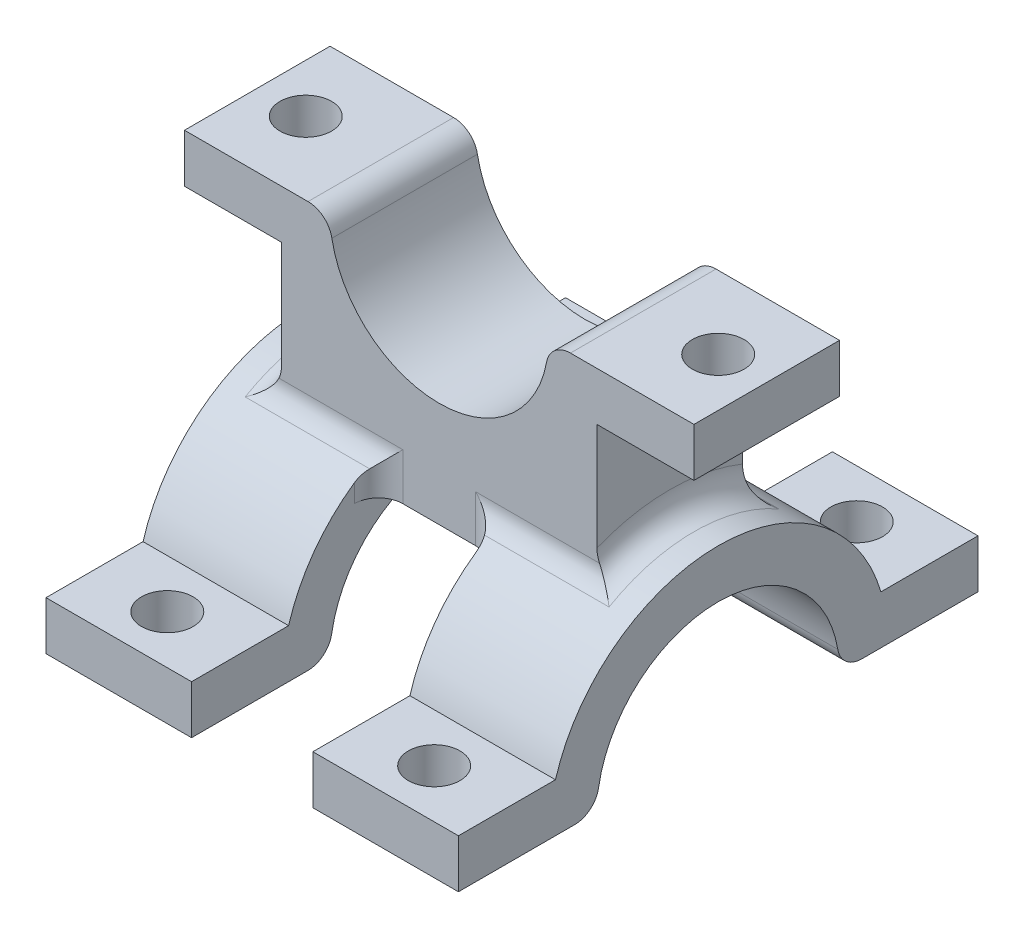
SolidWorks part; units mm, degrees
ref_plane "Front Plane" through (0, 0, 0) normal (0, 0, 1) x (1, 0, 0)
ref_plane "Top Plane" through (0, 0, 0) normal (0, 1, 0) x (1, 0, 0)
ref_plane "Right Plane" through (0, 0, 0) normal (1, 0, 0) x (0, 0, -1)
sketch "Sketch1" plane through (0, 0, 0) normal (0, 0, 1) x (1, 0, 0)
  line L0 (0, 0) -> (0, 50000) construction
  line L1 (-76.4961, 74.3576) -> (-37.8039, 99.7576) construction
  line L5 (-37.8039, 99.7576) -> (-241.0039, 99.7576) construction
  line L6 (-182.9308, 127.7976) -> (-163.8808, 127.7976)
  line L22 (-76.4961, 74.3576) -> (-241.0039, 74.3576) construction
  line L23 (-241.0039, 99.7576) -> (-241.0039, 74.3576) construction
  line L24 (-163.8808, 127.7976) -> (-163.8808, 121.4476)
  line L25 (-163.8808, 121.4476) -> (-176.5808, 121.4476)
  line L26 (-176.5808, 121.4476) -> (-176.5808, 99.7576)
  line L27 (-176.5808, 99.7576) -> (-217.8558, 99.7576)
  line L28 (-197.2183, 113.5101) -> (-197.2183, 99.7576) construction
  line L29 (-217.8558, 121.4476) -> (-217.8558, 99.7576)
  line L30 (-230.5558, 121.4476) -> (-217.8558, 121.4476)
  line L31 (-230.5558, 127.7976) -> (-230.5558, 121.4476)
  line L32 (-211.5058, 127.7976) -> (-230.5558, 127.7976)
  circle A0 centre (0, 0) radius 104.14 construction
  circle A1 centre (-197.2183, 127.7976) radius 11.1125 construction
  arc A5 (-182.9308, 127.7976) -> (-211.5058, 127.7976) centre (-197.2183, 127.7976) cw
  point P5 (-57.15, 87.0576)
  point P9 (57.15, 87.0576)
  point P11 (-57.15, 87.0576)
  point P26 (0, 0)
  point P27 (-197.2183, 109.4037)
  dimension "D1" = 208.28
  dimension "D2" = 22.225
  dimension "D6" = 25.4
  dimension "D7" = 14.2875
  dimension "D9" = 12.7
  dimension "D3" = 197.2183
  dimension "D4" = 127.7976
  dimension "D5" = 114.3
  dimension "D8" = 203.2
  dimension "D10" = 19.05
  dimension "D11" = 6.35
extrude "Boss-Extrude1" add sketch "Sketch1" along normal blind 19.05
sketch "Sketch7" plane through (0, 121.4476, 0) normal (0, -1, 0) x (1, 0, 0)
  line L0 (-176.5808, 19.05) -> (-163.8808, 19.05) construction
  line L1 (-163.8808, 19.05) -> (-163.8808, 0) construction
  line L2 (-197.2183, 12.7) -> (-197.2183, 50012.7) construction
  line L3 (-217.8558, 19.05) -> (-176.5808, 19.05) construction
  circle A0 centre (-170.2308, 9.525) radius 3.3782
  circle A1 centre (-224.2058, 9.525) radius 3.3782
  point P4 (-170.2308, 19.05)
  point P7 (-163.8808, 9.525)
  point P12 (-197.2183, 19.05)
  dimension "D1" = 6.7564
extrude "Cut-Extrude3" cut sketch "Sketch7" against normal through all
sketch "Sketch10" plane through (-163.8808, 0, 0) normal (1, 0, 0) x (0, 0, -1)
  line L0 (-19.05, 99.7576) -> (0, 99.7576) construction
  line L1 (6.35, 83.8826) -> (24.4735, 83.8826)
  line L2 (24.4735, 83.8826) -> (24.4735, 90.2326)
  line L3 (24.4735, 90.2326) -> (11.7735, 90.2326)
  line L4 (-9.525, 106.1076) -> (-9.525, 99.7576) construction
  line L5 (-25.4, 83.8826) -> (-43.5235, 83.8826)
  line L6 (-43.5235, 83.8826) -> (-43.5235, 90.2326)
  line L7 (-43.5235, 90.2326) -> (-30.8235, 90.2326)
  arc A2 (6.35, 83.8826) -> (-25.4, 83.8826) centre (-9.525, 83.8826) ccw
  arc A3 (11.7735, 90.2326) -> (-30.8235, 90.2326) centre (-9.525, 83.8826) ccw
  point P5 (-9.525, 99.7576)
  point P14 (-6.35, 109.7141)
  dimension "D1" = 15.875
  dimension "D2" = 6.35
  dimension "D3" = 12.7
  dimension "D4" = 6.35
extrude "Boss-Extrude3" add sketch "Sketch10" against normal blind 19.05 from offset 6.35 offset against normal yes
ref_plane "Plane3" through (-197.2183, 0, 0) normal (1, 0, 0) x (0, 0, -1)
mirror "Mirror3" about plane through (-197.2183, 0, 0) normal (1, 0, 0) of "Boss-Extrude3"
sketch "Sketch11" plane through (0, 90.2326, 0) normal (0, 1, 0) x (1, 0, 0)
  line L0 (-224.2058, -30.8235) -> (-224.2058, -43.5235) construction
  line L1 (-205.1558, -43.5235) -> (-224.2058, -43.5235) construction
  line L2 (-189.2808, -43.5235) -> (-170.2308, -43.5235) construction
  line L3 (-170.2308, -30.8235) -> (-170.2308, -43.5235) construction
  line L4 (-189.2808, 24.4735) -> (-170.2308, 24.4735) construction
  line L5 (-170.2308, 24.4735) -> (-170.2308, 11.7735) construction
  line L6 (-224.2058, 24.4735) -> (-224.2058, 11.7735) construction
  line L7 (-205.1558, 24.4735) -> (-224.2058, 24.4735) construction
  circle A0 centre (-179.7558, -37.1735) radius 3.3782
  circle A1 centre (-179.7558, 18.1235) radius 3.3782
  circle A2 centre (-214.6808, 18.1235) radius 3.3782
  circle A3 centre (-214.6808, -37.1735) radius 3.3782
  point P8 (-215.785, -32.9234)
  point P9 (0, 0)
  point P12 (-224.2058, -37.1735)
  point P15 (-214.6808, -43.5235)
  point P18 (-179.7558, -43.5235)
  point P21 (-170.2308, -37.1735)
  point P24 (-179.7558, 24.4735)
  point P27 (-170.2308, 18.1235)
  point P30 (-224.2058, 18.1235)
  point P33 (-214.6808, 24.4735)
  dimension "D1" = 6.7564
  dimension "D2" = 6.7564
  dimension "D3" = 6.7564
  dimension "D4" = 6.7564
extrude "Cut-Extrude4" cut sketch "Sketch11" against normal through all
fillet "Fillet4" radius 3.175 16 edges at (-211.5058, 127.7976, 9.525) (-182.9308, 127.7976, 9.525) (-214.6808, 83.8826, 25.4) (-179.7558, 83.8826, 25.4) (-214.6808, 83.8826, -6.35) (-179.7558, 83.8826, -6.35) (-189.2808, 101.8603, 19.05) (-205.1558, 101.8603, 19.05) (-205.1558, 101.8603, 0) (-189.2808, 101.8603, 0) (-176.5808, 106.1076, 9.525) (-217.8558, 106.1076, 9.525) (-211.5058, 103.963, 0) (-182.9308, 103.963, 0) (-182.9308, 103.963, 19.05) (-211.5058, 103.963, 19.05)
